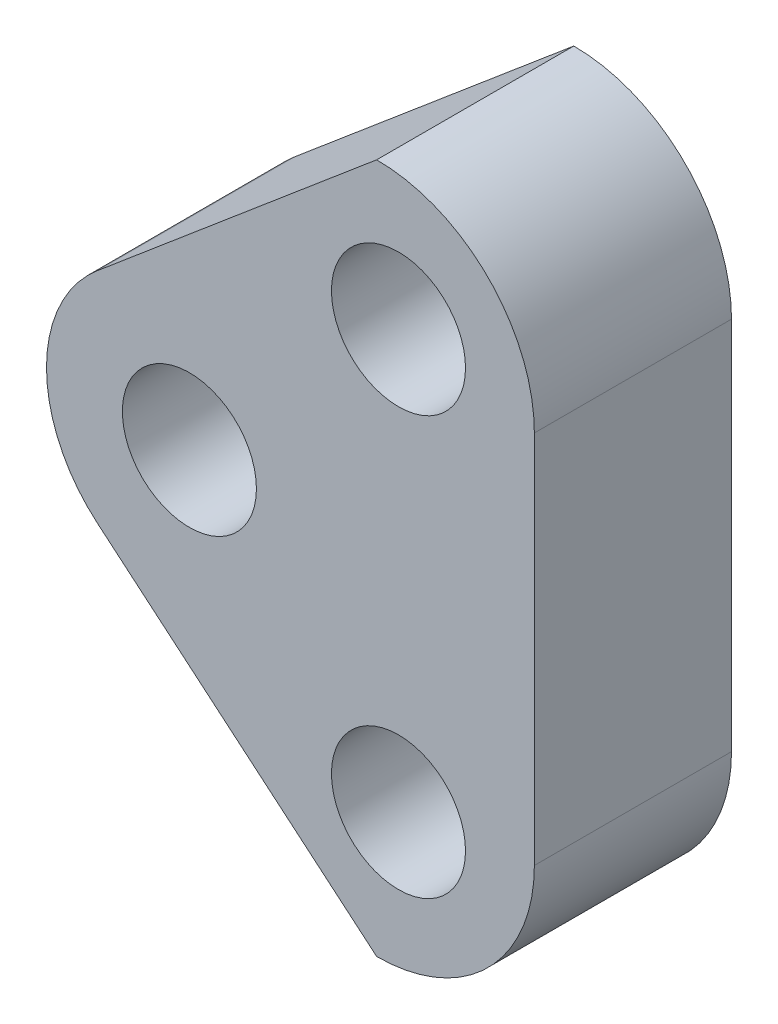
SolidWorks part; units mm, degrees
ref_plane "前视基准面" through (0, 0, 0) normal (0, 0, 1) x (1, 0, 0)
ref_plane "上视基准面" through (0, 0, 0) normal (0, 1, 0) x (1, 0, 0)
ref_plane "右视基准面" through (0, 0, 0) normal (1, 0, 0) x (0, 0, -1)
other "Configuration Table"
sketch "草图1" plane through (0, 0, 0) normal (0, 0, 1) x (1, 0, 0)
  line L1 (-9.5, -17.5) -> (9.5, -17.5)
  line L2 (-17.5, -9.5) -> (-17.5, 9.5)
  line L3 (-9.5, 17.5) -> (9.5, 17.5)
  line L4 (17.5, -9.5) -> (17.5, 9.5)
  line L5 (-17.5, -17.5) -> (17.5, 17.5) construction
  line L6 (-17.5, 17.5) -> (17.5, -17.5) construction
  circle A0 centre (0, 0) radius 15
  circle A1 centre (10.6066, 10.6066) radius 3.4
  circle A2 centre (10.6066, -10.6066) radius 3.4
  circle A3 centre (-10.6066, -10.6066) radius 3.4
  circle A4 centre (-10.6066, 10.6066) radius 3.4
  arc A5 (17.5, 9.5) -> (9.5, 17.5) centre (9.5, 9.5) ccw
  arc A6 (9.5, -17.5) -> (17.5, -9.5) centre (9.5, -9.5) ccw
  arc A7 (-9.5, -17.5) -> (-17.5, -9.5) centre (-9.5, -9.5) cw
  arc A8 (-17.5, 9.5) -> (-9.5, 17.5) centre (-9.5, 9.5) cw
  point P18 (0, 0)
  dimension "D1" = 30
  dimension "D2" = 6.8
  dimension "D6" = 8
  dimension "D3" = 35
  dimension "D4" = 35
  dimension "D5" = 4
extrude "凸台-拉伸1" add sketch "草图1" along normal blind 11 contours A4 A0 A3 A2 A1 | A8 L2 A7 L1 A6 L4 A5 L3 A4 A0 A1 A2 A3
sketch "草图2" plane through (0, 0, 0) normal (0, 0, -1) x (-1, 0, 0)
  circle A0 centre (10.6066, -10.6066) radius 3.4 construction
  circle A1 centre (-10.6066, -10.6066) radius 3.4 construction
  circle A2 centre (10.6066, 10.6066) radius 3.4 construction
  circle A3 centre (-10.6066, 10.6066) radius 3.4 construction
  circle A4 centre (10.6066, -10.6066) radius 3.4
  circle A5 centre (-10.6066, -10.6066) radius 3.4
  circle A6 centre (10.6066, 10.6066) radius 3.4
  circle A7 centre (-10.6066, 10.6066) radius 3.4
extrude "凸台-拉伸2" add sketch "草图2" against normal blind 3
sketch "草图3" plane through (0, 0, 11) normal (0, 0, 1) x (1, 0, 0)
  circle A0 centre (0, 0) radius 3.4
  dimension "D1" = 6.8
extrude "切除-拉伸1" cut sketch "草图3" against normal through all
sketch "草图4" plane through (0, 0, 0) normal (0, 0, -1) x (-1, 0, 0)
  circle A0 centre (0, 0) radius 6
  circle A1 centre (0, 0) radius 3.4 construction
  circle A2 centre (0, 0) radius 3.4
  dimension "D1" = 12
extrude "切除-拉伸2" cut sketch "草图4" against normal blind 5
sketch "草图6" plane through (0, 0, 0) normal (0, 0, -1) x (-1, 0, 0)
  line L0 (0, 17.5) -> (17.5, 0)
  line L1 (9.5, 17.5) -> (-9.5, 17.5) construction
  line L2 (17.5, -9.5) -> (17.5, 9.5) construction
  line L3 (17.5, 0) -> (0, -17.5)
  line L4 (9.5, -17.5) -> (-9.5, -17.5) construction
  line L9 (9.5, 17.5) -> (-9.5, 17.5)
  line L10 (-17.5, 9.5) -> (-17.5, -9.5)
  line L11 (-9.5, -17.5) -> (9.5, -17.5)
  line L12 (17.5, -9.5) -> (17.5, 9.5)
  line L13 (9.5, 17.5) -> (-9.5, 17.5)
  line L14 (-17.5, 9.5) -> (-17.5, -9.5)
  line L15 (-9.5, -17.5) -> (9.5, -17.5)
  line L16 (17.5, -9.5) -> (17.5, 9.5)
  arc A4 (17.5, 9.5) -> (9.5, 17.5) centre (9.5, 9.5) ccw
  arc A5 (-9.5, 17.5) -> (-17.5, 9.5) centre (-9.5, 9.5) ccw
  arc A6 (-17.5, -9.5) -> (-9.5, -17.5) centre (-9.5, -9.5) ccw
  arc A7 (9.5, -17.5) -> (17.5, -9.5) centre (9.5, -9.5) ccw
  arc A8 (17.5, 9.5) -> (9.5, 17.5) centre (9.5, 9.5) ccw
  arc A9 (-9.5, 17.5) -> (-17.5, 9.5) centre (-9.5, 9.5) ccw
  arc A10 (-17.5, -9.5) -> (-9.5, -17.5) centre (-9.5, -9.5) ccw
  arc A11 (9.5, -17.5) -> (17.5, -9.5) centre (9.5, -9.5) ccw
  arc M10 (17.5, 9.5) -> (9.5, 17.5) centre (9.5, 9.5) ccw
  line M11 (9.5, 17.5) -> (-9.5, 17.5)
  line M15 (-9.5, -17.5) -> (9.5, -17.5)
  arc M16 (9.5, -17.5) -> (17.5, -9.5) centre (9.5, -9.5) ccw
  line M17 (17.5, -9.5) -> (17.5, 9.5)
  dimension "D1" = 0
extrude "切除-拉伸3" cut sketch "草图6" against normal through all contours L0 M11 M17 M10 | L3 M17 M15 M16
sketch "草图7" plane through (0, 0, 11) normal (0, 0, 1) x (1, 0, 0)
  line L0 (17.5, -9.5) -> (17.5, 9.5) construction
  line L6 (0, -17.5) -> (9.5, -17.5)
  line L7 (-17.5, 0) -> (0, -17.5)
  line L8 (0, 17.5) -> (-17.5, 0)
  line L9 (9.5, 17.5) -> (0, 17.5)
  line L10 (17.5, -9.5) -> (17.5, 9.5)
  line L11 (0, -17.5) -> (9.5, -17.5)
  line L12 (-17.5, 0) -> (0, -17.5)
  line L13 (0, 17.5) -> (-17.5, 0)
  line L14 (9.5, 17.5) -> (0, 17.5)
  line L15 (17.5, -9.5) -> (17.5, 9.5)
  circle A0 centre (17.5, 0) radius 24.7487
  arc A3 (17.5, 9.5) -> (9.5, 17.5) centre (9.5, 9.5) ccw
  arc A4 (9.5, -17.5) -> (17.5, -9.5) centre (9.5, -9.5) ccw
  arc A5 (17.5, 9.5) -> (9.5, 17.5) centre (9.5, 9.5) ccw
  arc A6 (9.5, -17.5) -> (17.5, -9.5) centre (9.5, -9.5) ccw
  line M9 (-7.2226, -10.2774) -> (0, -17.5)
  line M15 (0, 17.5) -> (-7.2226, 10.2774)
  arc M16 (-7.2226, 10.2774) -> (-10.2774, 7.2226) centre (-10.6066, 10.6066) cw
  line M17 (-10.2774, 7.2226) -> (-17.5, 0)
  line M18 (-17.5, 0) -> (-10.2774, -7.2226)
  arc M19 (-10.2774, -7.2226) -> (-7.2226, -10.2774) centre (-10.6066, -10.6066) cw
  dimension "D1" = 0
extrude "切除-拉伸5" cut sketch "草图7" against normal through all contours A0 M15 M16 M17 M18 M19 M9 | L12 M19 | L13 M16
sketch "草图8" plane through (0, 0, 11) normal (0, 0, 1) x (1, 0, 0)
  line L3 (9.5, 17.5) -> (0, 17.5)
  line L4 (0, -17.5) -> (9.5, -17.5)
  line L5 (17.5, -9.5) -> (17.5, 9.5)
  line L6 (9.5, 17.5) -> (0, 17.5)
  line L7 (0, -17.5) -> (9.5, -17.5)
  line L8 (17.5, -9.5) -> (17.5, 9.5)
  circle A0 centre (0, 0) radius 3.4 construction
  circle A1 centre (0, 0) radius 3.4
  circle A2 centre (10.6066, 10.6066) radius 3.4 construction
  arc A3 (0, 17.5) -> (0, -17.5) centre (17.5, 0) ccw
  arc A4 (9.5, -17.5) -> (17.5, -9.5) centre (9.5, -9.5) ccw
  arc A5 (17.5, 9.5) -> (9.5, 17.5) centre (9.5, 9.5) ccw
  arc A6 (0, 17.5) -> (0, -17.5) centre (17.5, 0) ccw
  arc A7 (9.5, -17.5) -> (17.5, -9.5) centre (9.5, -9.5) ccw
  arc A8 (17.5, 9.5) -> (9.5, 17.5) centre (9.5, 9.5) ccw
  circle A9 centre (10.6066, 10.6066) radius 3.4
  circle A10 centre (10.6066, -10.6066) radius 3.4 construction
  circle A11 centre (10.6066, -10.6066) radius 3.4
  dimension "D1" = 0
extrude "凸台-拉伸3" add sketch "草图8" along normal blind 1
sketch "草图9" plane through (0, 0, 12) normal (0, 0, 1) x (1, 0, 0)
  line L3 (9.5, 17.5) -> (0, 17.5)
  line L4 (0, -17.5) -> (9.5, -17.5)
  line L5 (17.5, -9.5) -> (17.5, 9.5)
  line L6 (9.5, 17.5) -> (0, 17.5)
  line L7 (0, -17.5) -> (9.5, -17.5)
  line L8 (17.5, -9.5) -> (17.5, 9.5)
  arc A3 (17.5, 9.5) -> (9.5, 17.5) centre (9.5, 9.5) ccw
  arc A4 (0, 17.5) -> (0, -17.5) centre (17.5, 0) ccw
  arc A5 (9.5, -17.5) -> (17.5, -9.5) centre (9.5, -9.5) ccw
  arc A6 (17.5, 9.5) -> (9.5, 17.5) centre (9.5, 9.5) ccw
  arc A7 (0, 17.5) -> (0, -17.5) centre (17.5, 0) ccw
  arc A8 (9.5, -17.5) -> (17.5, -9.5) centre (9.5, -9.5) ccw
  dimension "D1" = 0
extrude "切除-拉伸6" cut sketch "草图9" against normal blind 1
sketch "草图10" plane through (0, 0, 0) normal (0, 0, -1) x (-1, 0, 0)
  line L3 (0, 17.5) -> (-9.5, 17.5)
  line L4 (-17.5, 9.5) -> (-17.5, -9.5)
  line L5 (-9.5, -17.5) -> (0, -17.5)
  line L6 (0, 17.5) -> (-9.5, 17.5)
  line L7 (-17.5, 9.5) -> (-17.5, -9.5)
  line L8 (-9.5, -17.5) -> (0, -17.5)
  arc A3 (0, -17.5) -> (0, 17.5) centre (-17.5, 0) ccw
  arc A4 (-9.5, 17.5) -> (-17.5, 9.5) centre (-9.5, 9.5) ccw
  arc A5 (-17.5, -9.5) -> (-9.5, -17.5) centre (-9.5, -9.5) ccw
  arc A6 (0, -17.5) -> (0, 17.5) centre (-17.5, 0) ccw
  arc A7 (-9.5, 17.5) -> (-17.5, 9.5) centre (-9.5, 9.5) ccw
  arc A8 (-17.5, -9.5) -> (-9.5, -17.5) centre (-9.5, -9.5) ccw
  dimension "D1" = 0
extrude "切除-拉伸7" cut sketch "草图10" against normal blind 1
sketch "草图11" plane through (0, 0, 1) normal (0, 0, -1) x (-1, 0, 0)
  line L0 (-9.5, 17.5) -> (4.6745, 5.5401)
  line L1 (-9.5, -17.5) -> (4.6745, -5.5401)
  line L3 (0, 17.5) -> (-9.5, 17.5)
  line L4 (-17.5, 9.5) -> (-17.5, -9.5)
  line L5 (-9.5, -17.5) -> (0, -17.5)
  line L6 (0, 17.5) -> (-9.5, 17.5)
  line L7 (-17.5, 9.5) -> (-17.5, -9.5)
  line L8 (-9.5, -17.5) -> (0, -17.5)
  circle A0 centre (0, 0) radius 7.2487
  arc A3 (0, -17.5) -> (0, 17.5) centre (-17.5, 0) ccw
  arc A4 (-9.5, 17.5) -> (-17.5, 9.5) centre (-9.5, 9.5) ccw
  arc A5 (-17.5, -9.5) -> (-9.5, -17.5) centre (-9.5, -9.5) ccw
  arc A6 (0, -17.5) -> (0, 17.5) centre (-17.5, 0) ccw
  arc A7 (-9.5, 17.5) -> (-17.5, 9.5) centre (-9.5, 9.5) ccw
  arc A8 (-17.5, -9.5) -> (-9.5, -17.5) centre (-9.5, -9.5) ccw
  arc M9 (0, -17.5) -> (0, 17.5) centre (-17.5, 0) ccw
  line M10 (0, 17.5) -> (-9.5, 17.5)
  line M14 (-9.5, -17.5) -> (0, -17.5)
  dimension "D1" = 0
extrude "切除-拉伸8" cut sketch "草图11" against normal blind 10 contours A0 L0 M9 M10 | A0 L1 M14 M9
sketch "草图12" plane through (0, 0, 1) normal (0, 0, -1) x (-1, 0, 0)
  circle A0 centre (0, 0) radius 3.25
  circle A1 centre (0, 0) radius 6 construction
  circle A2 centre (0, 0) radius 6
  dimension "D1" = 6.5
extrude "凸台-拉伸5" add sketch "草图12" against normal blind 4
move or copy body "实体-移动/复制1" [suppressed] bodies to move or copy 118 parameters "D1"=0, "D2"=0, "D3"=0
move or copy body "实体-移动/复制2" [suppressed] bodies to move or copy 119 parameters "D1"=0, "D2"=0, "D3"=0
